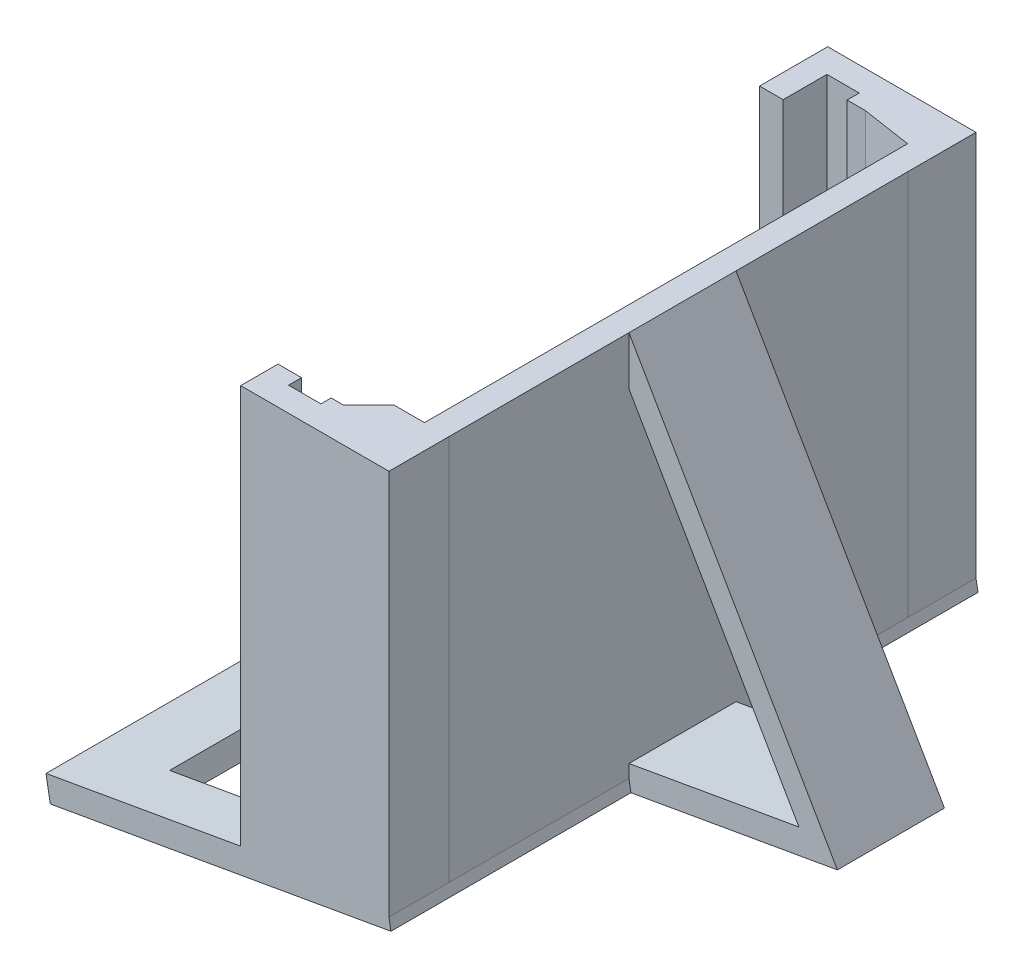
SolidWorks part; units mm, degrees
ref_plane "Front Plane" through (0, 0, 0) normal (0, 0, 1) x (1, 0, 0)
ref_plane "Top Plane" through (0, 0, 0) normal (0, 1, 0) x (1, 0, 0)
ref_plane "Right Plane" through (0, 0, 0) normal (1, 0, 0) x (0, 0, -1)
sketch "Sketch1" plane through (0, 0, 0) normal (0, 1, 0) x (1, 0, 0)
  line L1 (0, 0) -> (38.6999, 0)
  line L2 (0, 0) -> (0, 153.1937)
  line L3 (0, 153.1937) -> (38.6999, 153.1937)
  line L4 (38.6999, 0) -> (38.6999, 153.1937)
  dimension "D1" = 38.6999
  dimension "D2" = 153.1937
extrude "Boss-Extrude1" add sketch "Sketch1" along normal blind 0.0254
sketch "Sketch3" plane through (0, 0.0254, 0) normal (0, 1, 0) x (1, 0, 0)
  line L0 (6.65, 146.8438) -> (6.15, 146.8438)
  line L1 (6.65, 146.8438) -> (14.5875, 146.8438)
  line L2 (14.5875, 146.8438) -> (14.5875, 143.6687)
  line L3 (14.5875, 143.6687) -> (32.05, 143.6687)
  line L4 (6.15, 146.8438) -> (6.15, 135.4137)
  line L7 (32.05, 143.6687) -> (32.35, 143.6687)
  line L8 (32.35, 143.6687) -> (32.35, 135.4137)
  line L9 (32.35, 135.4137) -> (38.7, 135.4137)
  line L10 (38.7, 135.4137) -> (38.7, 153.1937)
  line L11 (38.7, 153.1937) -> (0, 153.1937)
  line L12 (6.15, 135.4137) -> (0, 135.4137)
  line L13 (0, 153.1937) -> (0, 135.4137)
  line L15 (0, 153.1937) -> (38.6999, 153.1937) construction
  line L16 (14.5875, 9.025) -> (17.7625, 9.025)
  line L17 (10.6187, 146.8438) -> (10.6187, 76.5969) construction
  line L18 (10.6187, 76.5969) -> (61.4187, 76.5969) construction
  line L19 (38.6999, 0) -> (0, 0)
  line L20 (38.6999, 15.6157) -> (38.6999, 0)
  line L25 (14.5875, 6.35) -> (14.5875, 9.025)
  line L26 (6.65, 6.35) -> (14.5875, 6.35)
  line L27 (6.65, 6.35) -> (6.15, 6.35)
  line L28 (6.15, 6.35) -> (6.15, 9.7407)
  line L29 (6.15, 9.7407) -> (0, 9.7407)
  line L30 (0, 0) -> (0, 9.7407)
  line L31 (17.7625, 9.025) -> (24.3532, 15.6157)
  line L32 (24.3532, 15.6157) -> (38.6999, 15.6157)
  line L33 (19.35, 143.6687) -> (32.35, 141.6844)
  line L34 (38.6999, 0) -> (38.6999, 153.1937) construction
  line L35 (0, 0) -> (38.6999, 0) construction
  point P19 (10.6187, 146.8438)
  point P35 (6.0151, 12.0552)
  point P36 (0, 0)
  dimension "D1" = 17.4625
  dimension "D2" = 7.9375
  dimension "D3" = 3.175
  dimension "D4" = 11.43
  dimension "D5" = 0.5
  dimension "D6" = 0.3
  dimension "D7" = 0
  dimension "D8" = 38.6999
  dimension "D9" = 6.15
  dimension "D10" = 6.35
  dimension "D11" = 6.35
  dimension "D12" = 6.35
  dimension "D13" = 70.2469
  dimension "D14" = 50.8
  dimension "D15" = 3.175
  dimension "D16" = 135
  dimension "D17" = 14.3467
  dimension "D18" = 90
  dimension "D19" = 90
  dimension "D20" = 90
  dimension "D21" = 4.7625
  dimension "D22" = 1.9844
  dimension "D23" = 0
  dimension "D24" = 270
  dimension "D25" = 9.7407
  dimension "D26" = 6.5907
  dimension "D27" = 90
  dimension "D28" = 2.675
extrude "Boss-Extrude2" add sketch "Sketch3" along normal blind 104.14
sketch "Sketch6" plane through (0, 0, -135.4137) normal (0, 0, 1) x (1, 0, 0)
  line L1 (32.35, 104.1654) -> (38.7, 104.1654)
  line L2 (32.35, 104.1654) -> (32.35, 0.0254)
  line L3 (32.35, 0.0254) -> (38.7, 0.0254)
  line L4 (38.7, 104.1654) -> (38.7, 0.0254)
  dimension "D1" = 104.14
  dimension "D2" = 6.35
extrude "Boss-Extrude3" add sketch "Sketch6" along normal up to surface (119.798 mm away) up to face at (31.5266, 52.0954, -15.6157)
sketch "Sketch15" plane through (0, 0, 0) normal (0, 0, 1) x (1, 0, 0)
  line L0 (0, 0) -> (38.6999, 0) construction
  line L1 (-50.8, -8.8719) -> (-49.6803, -15.2219)
  line L2 (127, 22.479) -> (-127, -22.3081) construction
  line L3 (0, 104.1654) -> (0, 0) construction
  line L4 (-49.6803, -15.2219) -> (39.2197, 0.4535)
  line L5 (39.2197, 0.4535) -> (38.1, 6.8035)
  line L6 (38.1, 6.8035) -> (-50.8, -8.8719)
  dimension "D1" = 10
  dimension "D2" = 254
  dimension "D3" = 127
  dimension "D4" = 22.479
  dimension "D5" = 6.35
  dimension "D6" = 88.9
  dimension "D7" = 38.1
extrude "Boss-Extrude7" add sketch "Sketch15" against normal up to surface (153.1938 mm away) up to face at (19.35, 52.0827, -153.1937)
sketch "Sketch11" plane through (0, 0, -153.1937) normal (0, 0, -1) x (-1, 0, 0)
  line L0 (-38.6999, 104.1654) -> (-93.0935, 9.9529)
  line L1 (-38.6999, 104.1654) -> (-38.6999, 3.4011) construction
  line L2 (-38.6999, 104.1654) -> (0, 104.1654) construction
  line L4 (-38.6999, 91.4654) -> (-86.4387, 8.7795)
  line L5 (-86.4387, 8.7795) -> (-93.0935, 9.9529)
  line L6 (-38.6999, 91.4654) -> (-38.6999, 104.1654)
  line L7 (49.6803, -15.2219) -> (-36.6476, 0) construction
  point P7 (-102.9801, -2.1166)
  point P11 (-99.1731, -7.1867)
  dimension "D1" = 12.7
  dimension "D2" = 30
  dimension "D3" = 0
  dimension "D4" = 30
  dimension "D5" = 12.7
  dimension "D6" = 0
extrude "Boss-Extrude5" add sketch "Sketch11" along direction (0, 0, -1) on the side against the normal blind 27.94 from offset 62.6269 contours L6 L0 L5 L4 offset against normal yes
sketch "Sketch14" plane through (0, 0, -153.1937) normal (0, 0, -1) x (-1, 0, 0)
  line L1 (-26, 40.005) -> (-14.5875, 40.005)
  line L2 (-26, 40.005) -> (-26, 59.055)
  line L3 (-26, 59.055) -> (-14.5875, 59.055)
  line L4 (-14.5875, 40.005) -> (-14.5875, 59.055)
  line L6 (-14.5875, 104.1654) -> (-14.5875, 2.6576) construction
  line L7 (-32.35, 104.1654) -> (-32.35, 5.7897) construction
  line L8 (0, 0.0855) -> (0, 104.1654) construction
  line L9 (0, 104.1654) -> (0, 0.0855) construction
  line L10 (0, 0.0855) -> (-39.2846, 0.0855) construction
  line L11 (-39.2197, 0.4535) -> (-38.6999, 3.4011) construction
  dimension "D1" = 19.05
  dimension "D2" = 39.9195
  dimension "D3" = 0
  dimension "D4" = 6.35
  dimension "D5" = 0
extrude "Cut-Extrude1" cut sketch "Sketch14" against normal up to next
sketch "Sketch18" plane through (38.1146, 6.7206, 0) normal (0.9848, 0.1736, 0) x (0, 0, -1)
  line L0 (153.1937, -6.3638) -> (0, -6.3638) construction
  line L1 (62.6269, -6.3638) -> (90.5669, -6.3638)
  line L2 (62.6269, -6.3638) -> (62.6269, -0.0138)
  line L3 (62.6269, -0.0138) -> (90.5669, -0.0138)
  line L4 (90.5669, -6.3638) -> (90.5669, -0.0138)
  line L5 (90.5669, 83.3556) -> (90.5669, -6.3638) construction
  dimension "D1" = 27.94
  dimension "D2" = 0
  dimension "D3" = 6.35
extrude "Boss-Extrude8" add sketch "Sketch18" along normal up to next
sketch "Sketch19" plane through (-0.0146, 0.0829, 0) normal (-0.1736, 0.9848, 0) x (0.9848, 0.1736, 0)
  line L0 (-51.5688, 153.1937) -> (-51.5688, 0) construction
  line L1 (-32.5188, 134.1437) -> (-13.4688, 134.1437)
  line L2 (-32.5188, 134.1437) -> (-32.5188, 115.0937)
  line L3 (-32.5188, 115.0937) -> (-13.4688, 115.0937)
  line L4 (-13.4688, 134.1437) -> (-13.4688, 115.0937)
  line L5 (0.0148, 153.1937) -> (-51.5688, 153.1937) construction
  line L6 (-32.5188, 108.7437) -> (-32.5188, 89.6937)
  line L7 (-32.5188, 108.7437) -> (-13.4688, 108.7437)
  line L8 (-13.4688, 108.7437) -> (-13.4688, 89.6937)
  line L9 (-32.5188, 89.6937) -> (-13.4688, 89.6937)
  line L10 (-32.5188, 83.3438) -> (-32.5188, 64.2938)
  line L11 (-32.5188, 83.3438) -> (-13.4688, 83.3438)
  line L12 (-13.4688, 83.3438) -> (-13.4688, 64.2938)
  line L13 (-32.5188, 64.2938) -> (-13.4688, 64.2938)
  line L14 (-32.5188, 57.9438) -> (-32.5188, 38.8938)
  line L15 (-32.5188, 57.9438) -> (-13.4688, 57.9438)
  line L16 (-13.4688, 57.9438) -> (-13.4688, 38.8938)
  line L17 (-32.5188, 38.8938) -> (-13.4688, 38.8938)
  line L18 (-32.5188, 32.5438) -> (-32.5188, 13.4938)
  line L19 (-32.5188, 32.5438) -> (-13.4688, 32.5438)
  line L20 (-13.4688, 32.5438) -> (-13.4688, 13.4938)
  line L21 (-32.5188, 13.4938) -> (-13.4688, 13.4938)
  dimension "D1" = 19.05
  dimension "D2" = 19.05
  dimension "D3" = 19.05
  dimension "D4" = 19.05
  dimension "D6" = 6.35
  dimension "D5" = 5
extrude "Cut-Extrude2" cut sketch "Sketch19" against normal through all
sketch "Sketch20" plane through (1.1051, -6.2671, 0) normal (0.1736, -0.9848, 0) x (0.9848, 0.1736, 0)
  line L1 (-47.8769, 185.4188) -> (88.0421, 185.4188)
  line L2 (-47.8769, 185.4188) -> (-47.8769, -314.6402)
  line L3 (-47.8769, -314.6402) -> (88.0421, -314.6402)
  line L4 (88.0421, 185.4188) -> (88.0421, -314.6402)
extrude "Cut-Extrude3" cut sketch "Sketch20" along normal blind 153.162
